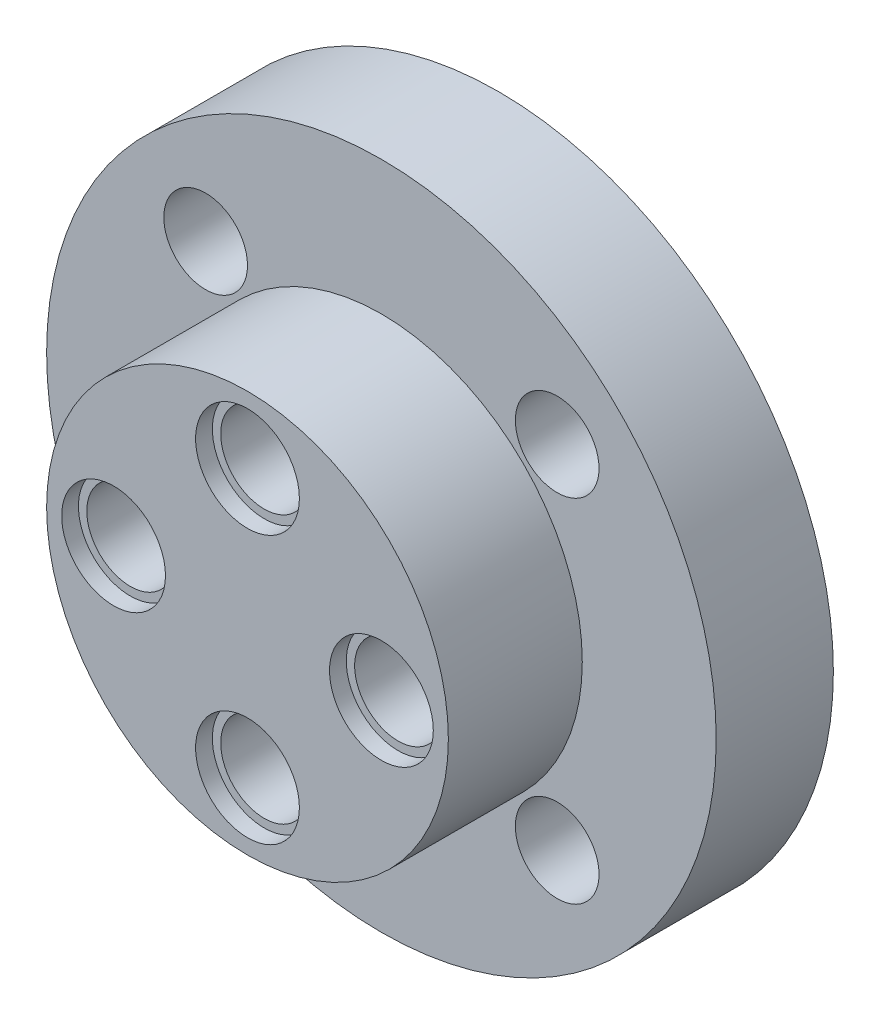
SolidWorks part; units mm, degrees
ref_plane "Спереди" through (0, 0, 0) normal (0, 0, 1) x (1, 0, 0)
ref_plane "Сверху" through (0, 0, 0) normal (0, 1, 0) x (1, 0, 0)
ref_plane "Справа" through (0, 0, 0) normal (1, 0, 0) x (0, 0, -1)
other "Configuration Table"
sketch "Эскиз1" plane through (0, 0, 0) normal (0, 0, 1) x (1, 0, 0)
  line L1 (-10.5, -10.5) -> (10.5, -10.5) construction
  line L2 (-10.5, -10.5) -> (-10.5, 10.5) construction
  line L3 (-10.5, 10.5) -> (10.5, 10.5) construction
  line L4 (10.5, -10.5) -> (10.5, 10.5) construction
  line L5 (-10.5, -10.5) -> (10.5, 10.5) construction
  line L6 (-10.5, 10.5) -> (10.5, -10.5) construction
  circle A0 centre (-10.5, 10.5) radius 2.5
  circle A1 centre (10.5, 10.5) radius 2.5
  circle A2 centre (10.5, -10.5) radius 2.5
  circle A3 centre (-10.5, -10.5) radius 2.5
  circle A4 centre (0, 0) radius 20
  point P0 (0, 0)
  dimension "D2" = 5
  dimension "D3" = 40
  dimension "D1" = 21
extrude "Бобышка-Вытянуть1" add sketch "Эскиз1" along normal blind 7 contours A4 | A1 | A2 | A3 | A0
sketch "Эскиз2" plane through (0, 0, 7) normal (0, 0, 1) x (1, 0, 0)
  circle A0 centre (0, 0) radius 12
  dimension "D1" = 24
extrude "Бобышка-Вытянуть2" add sketch "Эскиз2" along normal blind 8
sketch "Эскиз3" plane through (0, 0, 15) normal (0, 0, 1) x (1, 0, 0)
  line L0 (0, 12) -> (0, -12) construction
  line L1 (-12, 0) -> (12, 0) construction
  circle A0 centre (0, 0) radius 12 construction
  circle A1 centre (0, 0) radius 12 construction
  circle A2 centre (0, 0) radius 8 construction
  circle A3 centre (-8, 0) radius 2.6
  circle A4 centre (0, 8) radius 2.6
  circle A5 centre (8, 0) radius 2.6
  circle A6 centre (0, -8) radius 2.6
  dimension "D1" = 16
  dimension "D2" = 5.2
extrude "Вырез-Вытянуть1" cut sketch "Эскиз3" against normal blind 7
sketch "Эскиз4" plane through (0, 0, 15) normal (0, 0, 1) x (1, 0, 0)
  circle A0 centre (-8, 0) radius 3.1
  circle A1 centre (0, 8) radius 3.1
  circle A2 centre (8, 0) radius 3.1
  circle A3 centre (0, -8) radius 3.1
  dimension "D1" = 6.2
extrude "Вырез-Вытянуть2" cut sketch "Эскиз4" against normal blind 1
sketch "Эскиз6" plane through (0, 0, 8) normal (0, 0, 1) x (1, 0, 0)
  circle A0 centre (8, 0) radius 3.1
  circle A1 centre (0, 8) radius 3.1
  circle A2 centre (-8, 0) radius 3.1
  circle A3 centre (0, -8) radius 3.1
  dimension "D1" = 6.2
extrude "Вырез-Вытянуть3" cut sketch "Эскиз6" against normal blind 1
